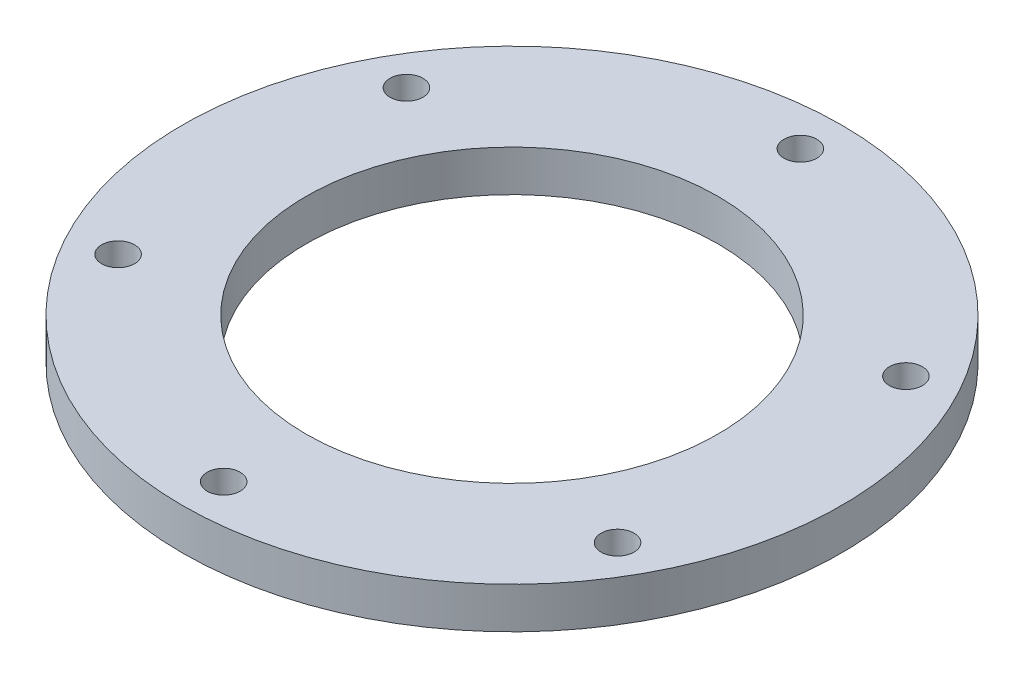
SolidWorks part; units mm, degrees
ref_plane "前视基准面" through (0, 0, 0) normal (0, 0, 1) x (1, 0, 0)
ref_plane "上视基准面" through (0, 0, 0) normal (0, 1, 0) x (1, 0, 0)
ref_plane "右视基准面" through (0, 0, 0) normal (1, 0, 0) x (0, 0, -1)
sketch "草图1" plane through (0, 0, 0) normal (0, 1, 0) x (1, 0, 0)
  circle A0 centre (0, 0) radius 25
  circle A1 centre (0, 0) radius 40
  circle A2 centre (0, 0) radius 35
  circle A3 centre (0, 35) radius 2
  circle A5 centre (30.3109, 17.5) radius 2
  circle A7 centre (30.3109, -17.5) radius 2
  circle A9 centre (0, -35) radius 2
  circle A11 centre (-30.3109, -17.5) radius 2
  circle A13 centre (-30.3109, 17.5) radius 2
  circle A15 centre (17.5, 30.3109) radius 2 [skipped]
  circle A16 centre (35, 0) radius 2 [skipped]
  circle A17 centre (17.5, -30.3109) radius 2 [skipped]
  circle A18 centre (-17.5, -30.3109) radius 2 [skipped]
  circle A19 centre (-35, 0) radius 2 [skipped]
  circle A20 centre (-17.5, 30.3109) radius 2 [skipped]
  point P31 (0, 0)
  dimension "D1" = 50
  dimension "D2" = 80
  dimension "D3" = 70
  dimension "D4" = 4
  dimension "D5" = 12
extrude "凸台-拉伸1" add sketch "草图1" along normal blind 5
